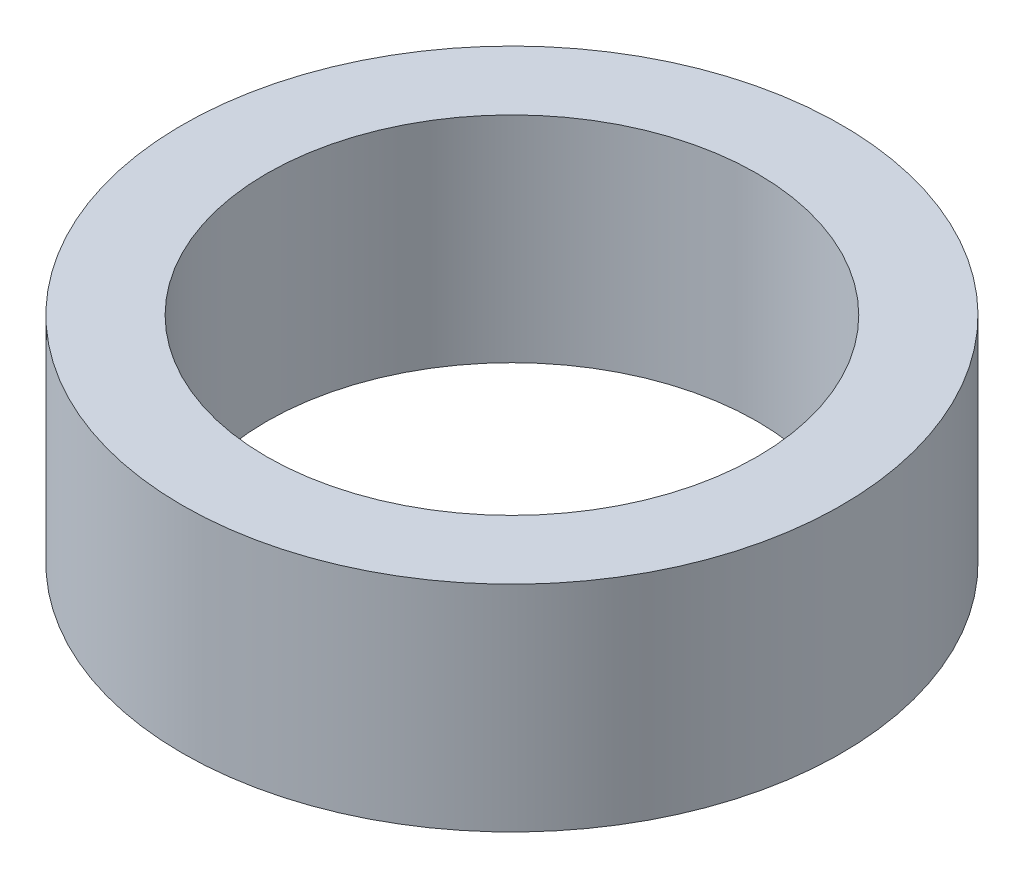
SolidWorks part; units mm, degrees
ref_plane "Front Plane" through (0, 0, 0) normal (0, 0, 1) x (1, 0, 0)
ref_plane "Top Plane" through (0, 0, 0) normal (0, 1, 0) x (1, 0, 0)
ref_plane "Right Plane" through (0, 0, 0) normal (1, 0, 0) x (0, 0, -1)
sketch "Sketch1" plane through (0, 0, 0) normal (0, 1, 0) x (1, 0, 0)
  circle A0 centre (0, 0) radius 21.5
  circle A1 centre (0, 0) radius 16
  dimension "D1" = 43
  dimension "D2" = 32
extrude "Boss-Extrude1" add sketch "Sketch1" along normal blind 14
